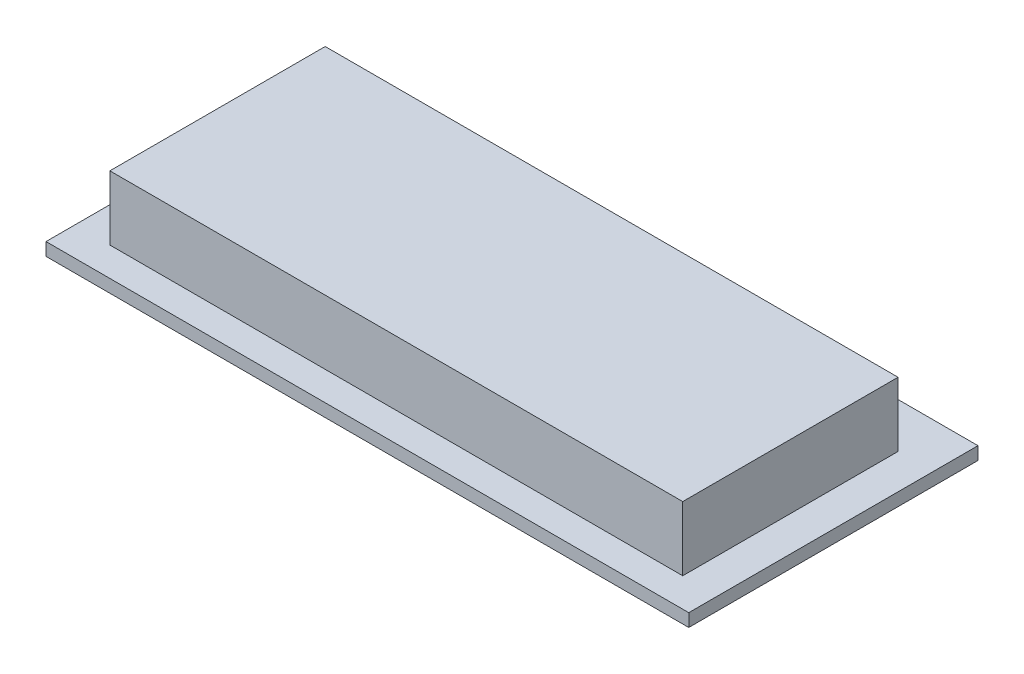
SolidWorks part; units mm, degrees
ref_plane "Front Plane" through (0, 0, 0) normal (0, 0, 1) x (1, 0, 0)
ref_plane "Top Plane" through (0, 0, 0) normal (0, 1, 0) x (1, 0, 0)
ref_plane "Right Plane" through (0, 0, 0) normal (1, 0, 0) x (0, 0, -1)
sketch "Sketch1" plane through (0, 0, 0) normal (0, 1, 0) x (1, 0, 0)
  line L1 (-79, 42.1385) -> (1, 42.1385)
  line L2 (-79, 42.1385) -> (-79, 6.1385)
  line L3 (-79, 6.1385) -> (1, 6.1385)
  line L4 (1, 42.1385) -> (1, 6.1385)
  dimension "D1" = 80
  dimension "D2" = 36
extrude "Boss-Extrude1" add sketch "Sketch1" along normal blind 1.6
sketch "Sketch2" plane through (0, 1.6, 0) normal (0, 1, 0) x (1, 0, 0)
  line L0 (-79, 6.1385) -> (1, 6.1385) construction
  line L1 (-74.65, 36.5385) -> (-3.35, 36.5385)
  line L2 (-74.65, 36.5385) -> (-74.65, 9.7385)
  line L3 (-74.65, 9.7385) -> (-3.35, 9.7385)
  line L4 (-3.35, 36.5385) -> (-3.35, 9.7385)
  line L5 (-79, 42.1385) -> (-79, 6.1385) construction
  dimension "D1" = 71.3
  dimension "D2" = 26.8
  dimension "D3" = 3.6
  dimension "D4" = 4.35
extrude "Boss-Extrude2" add sketch "Sketch2" along normal blind 8
